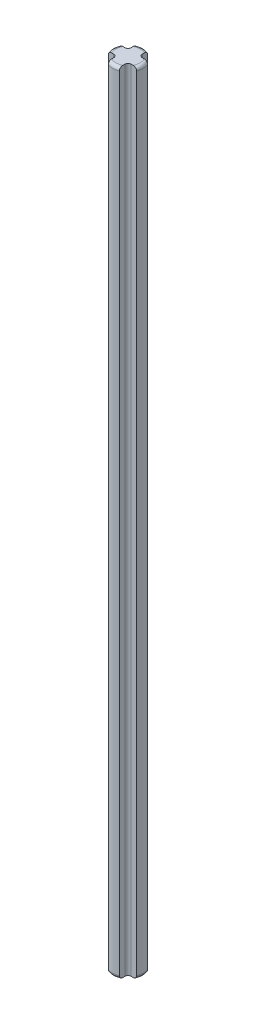
SolidWorks part; units mm, degrees
ref_plane "Front Plane" through (0, 0, 0) normal (0, 0, 1) x (1, 0, 0)
ref_plane "Top Plane" through (0, 0, 0) normal (0, 1, 0) x (1, 0, 0)
ref_plane "Right Plane" through (0, 0, 0) normal (1, 0, 0) x (0, 0, -1)
ref_plane "Plane1" through (0, 0, 0) normal (0, 0, -1) x (-1, 0, 0)
sketch "Sketch1" plane through (0, 0, 0) normal (0, 0, -1) x (-1, 0, 0)
  line L0 (-2.39, 0) -> (0, 0)
  line L1 (0, 0) -> (0, 124)
  line L2 (0, 124) -> (-2.39, 124)
  line L3 (-2.39, 124) -> (-2.39, 0)
  line L4 (0, 0) -> (0, 124) construction
  dimension "D1" = 2.39
  dimension "D2" = 124
revolve "Revolve1" add sketch "Sketch1" angle 360 about L4
sketch "Sketch2" plane through (0, 0, 0) normal (0, -1, 0) x (1, 0, 0)
  line L0 (0.875, 2.2241) -> (0.875, 0.875)
  line L1 (0.875, 0.875) -> (2.2241, 0.875)
  line L2 (2.629, 0) -> (-2.629, 0) construction
  line L3 (0, -2.629) -> (0, 2.629) construction
  line L4 (-2.39, 0) -> (2.39, 0) construction
  line L5 (0, 2.39) -> (0, -2.39) construction
  line L6 (0.875, -0.875) -> (2.2241, -0.875)
  line L7 (0.875, -2.2241) -> (0.875, -0.875)
  line L8 (-0.875, -2.2241) -> (-0.875, -0.875)
  line L9 (-0.875, -0.875) -> (-2.2241, -0.875)
  line L10 (-0.875, 0.875) -> (-2.2241, 0.875)
  line L11 (-0.875, 2.2241) -> (-0.875, 0.875)
  arc A0 (2.2241, 0.875) -> (0.875, 2.2241) centre (0, 0) ccw
  circle A1 centre (0, 0) radius 1.2374 construction
  circle A3 centre (0, 0) radius 2.39 construction
  arc A4 (2.2241, -0.875) -> (0.875, -2.2241) centre (0, 0) cw
  arc A5 (-2.2241, -0.875) -> (-0.875, -2.2241) centre (0, 0) ccw
  arc A6 (-2.2241, 0.875) -> (-0.875, 2.2241) centre (0, 0) cw
  dimension "D2" = 2.39
  dimension "D1" = 2.4749
  dimension "D3" = 1.3491
extrude "Cut-Extrude1" cut sketch "Sketch2" against normal through all
fillet "Fillet1" radius 0.5 12 edges at (2.39, 0, 0) (0, 0, 2.39) (0, 124, 2.39) (0.875, 62, 0.875) (2.39, 124, 0) (-2.39, 124, 0) (0, 124, -2.39) (0.875, 62, -0.875) (-0.875, 62, -0.875) (0, 0, -2.39) (-2.39, 0, 0) (-0.875, 62, 0.875)
sketch "Sketch6" [suppressed] plane through (0, 124, 0) normal (0, 1, 0) x (1, 0, 0)
  circle A0 centre (0, 0) radius 2.5795
extrude "Cut-Extrude5" [suppressed] cut sketch "Sketch6" against normal blind 91.74
fillet "Fillet2" [suppressed] radius 0.5
